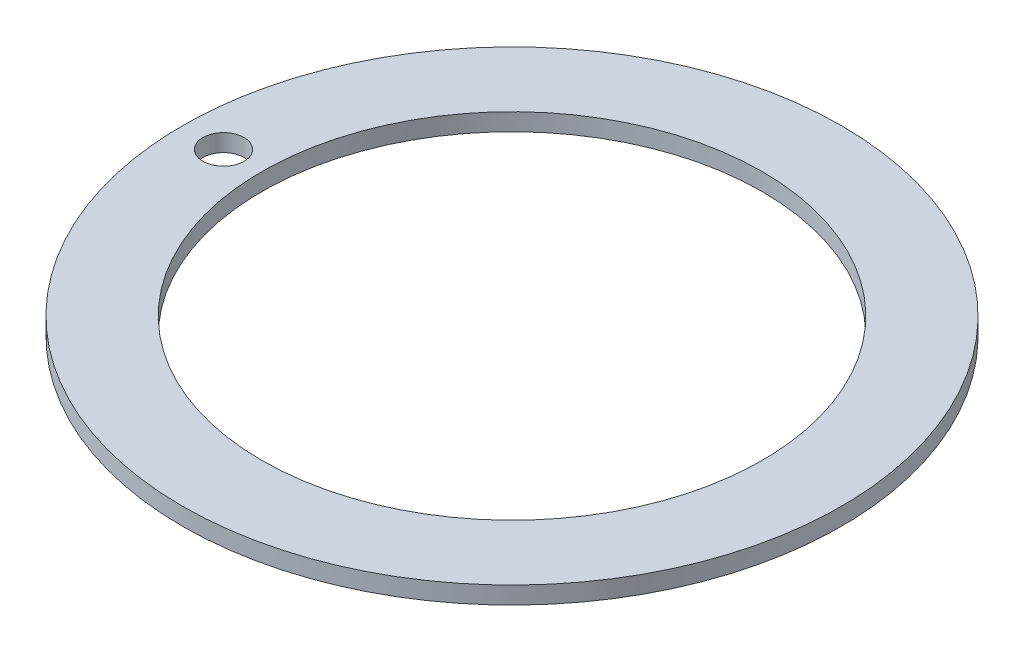
SolidWorks part; units mm, degrees
ref_plane "Front Plane" through (0, 0, 0) normal (0, 0, 1) x (1, 0, 0)
ref_plane "Top Plane" through (0, 0, 0) normal (0, 1, 0) x (1, 0, 0)
ref_plane "Right Plane" through (0, 0, 0) normal (1, 0, 0) x (0, 0, -1)
sketch "Sketch1" plane through (0, 0, 0) normal (0, 1, 0) x (1, 0, 0)
  circle A0 centre (0, 0) radius 38.0746
  circle A1 centre (0, 0) radius 28.9052
  dimension "D1" = 57.8104
  dimension "D2" = 76.1492
extrude "Boss-Extrude1" add sketch "Sketch1" along normal blind 2.0066
sketch "Sketch2" plane through (0, 2.0066, 0) normal (0, 1, 0) x (1, 0, 0)
  circle A0 centre (-33.3299, 0) radius 2.3812
  point P2 (-34.0961, 0)
  point P3 (0, 0)
  point P4 (-33.7769, 0)
  point P5 (0, 0)
  point P6 (0, 0)
  point P7 (-31.4783, -0.5108)
  point P8 (-33.3299, 0)
extrude "Cut-Extrude2" cut sketch "Sketch2" against normal blind 2.54
